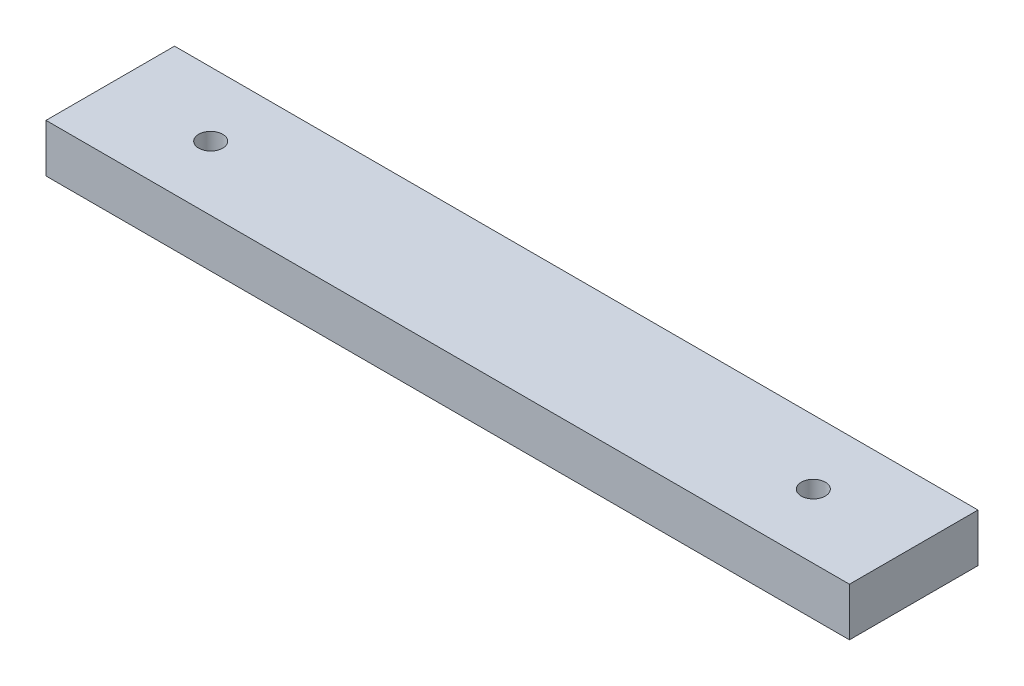
SolidWorks part; units mm, degrees
ref_plane "前基準面" through (0, 0, 0) normal (0, 0, 1) x (1, 0, 0)
ref_plane "上基準面" through (0, 0, 0) normal (0, 1, 0) x (1, 0, 0)
ref_plane "右基準面" through (0, 0, 0) normal (1, 0, 0) x (0, 0, -1)
sketch "草圖1" plane through (0, 0, 0) normal (0, 1, 0) x (1, 0, 0)
  line L1 (50, 8) -> (-50, 8)
  line L2 (50, 8) -> (50, -8)
  line L3 (50, -8) -> (-50, -8)
  line L4 (-50, 8) -> (-50, -8)
  line L5 (0, -8) -> (0, 8) construction
  line L6 (50, 0) -> (-50, 0) construction
  circle A0 centre (-37.5, 0) radius 1.5
  circle A1 centre (37.5, 0) radius 1.5
  point P0 (0, 0)
  dimension "D3" = 3
  dimension "D1" = 100
  dimension "D2" = 16
  dimension "D5" = 12.5
extrude "填料-伸長1" add sketch "草圖1" along normal blind 6
